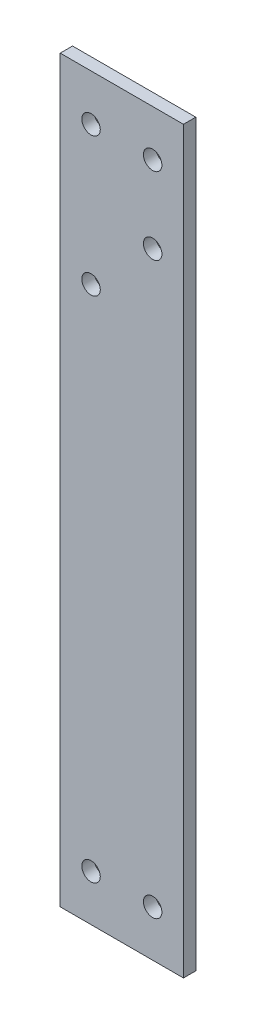
SolidWorks part; units mm, degrees
ref_plane "Plan de face" through (0, 0, 0) normal (0, 0, 1) x (1, 0, 0)
ref_plane "Plan de dessus" through (0, 0, 0) normal (0, 1, 0) x (1, 0, 0)
ref_plane "Plan de droite" through (0, 0, 0) normal (1, 0, 0) x (0, 0, -1)
sketch "Esquisse1" plane through (0, 0, 0) normal (0, 0, 1) x (1, 0, 0)
  line L1 (-10, 60) -> (10, 60)
  line L2 (-10, 60) -> (-10, -60)
  line L3 (-10, -60) -> (10, -60)
  line L4 (10, 60) -> (10, -60)
  line L5 (-10, 60) -> (10, -60) construction
  line L6 (-10, -60) -> (10, 60) construction
  point P0 (0, 0)
  dimension "D1" = 120
  dimension "D2" = 20
extrude "Extrusion1" add sketch "Esquisse1" along normal blind 2
sketch "Esquisse2" plane through (0, 0, 2) normal (0, 0, 1) x (1, 0, 0)
  line L0 (-10, 60) -> (-10, -60) construction
  line L1 (10, 60) -> (-10, 60) construction
  circle A0 centre (-5, 52.5) radius 1.5
  dimension "D3" = 3
  dimension "D1" = 5
  dimension "D2" = 7.5
extrude "Extrusion2" cut sketch "Esquisse2" against normal blind 2
sketch "Esquisse3" plane through (0, 0, 2) normal (0, 0, 1) x (1, 0, 0)
  line L0 (10, -60) -> (10, 60) construction
  line L1 (10, 60) -> (-10, 60) construction
  circle A0 centre (5, 52.5) radius 1.5
  dimension "D1" = 3
  dimension "D2" = 5
  dimension "D3" = 7.5
extrude "Extrusion3" cut sketch "Esquisse3" against normal blind 2
pattern_linear "Répétition linéaire1" count 2 spacing 105 along (0, -1, 0) of "Extrusion2", "Extrusion3"
sketch "Esquisse4" plane through (0, 0, 0) normal (0, 0, -1) x (-1, 0, 0)
  circle A0 centre (-5, 40) radius 1.5
  circle A1 centre (5, 30) radius 1.5
extrude "Enlèv. mat.-Extru.1" cut sketch "Esquisse4" against normal through all
